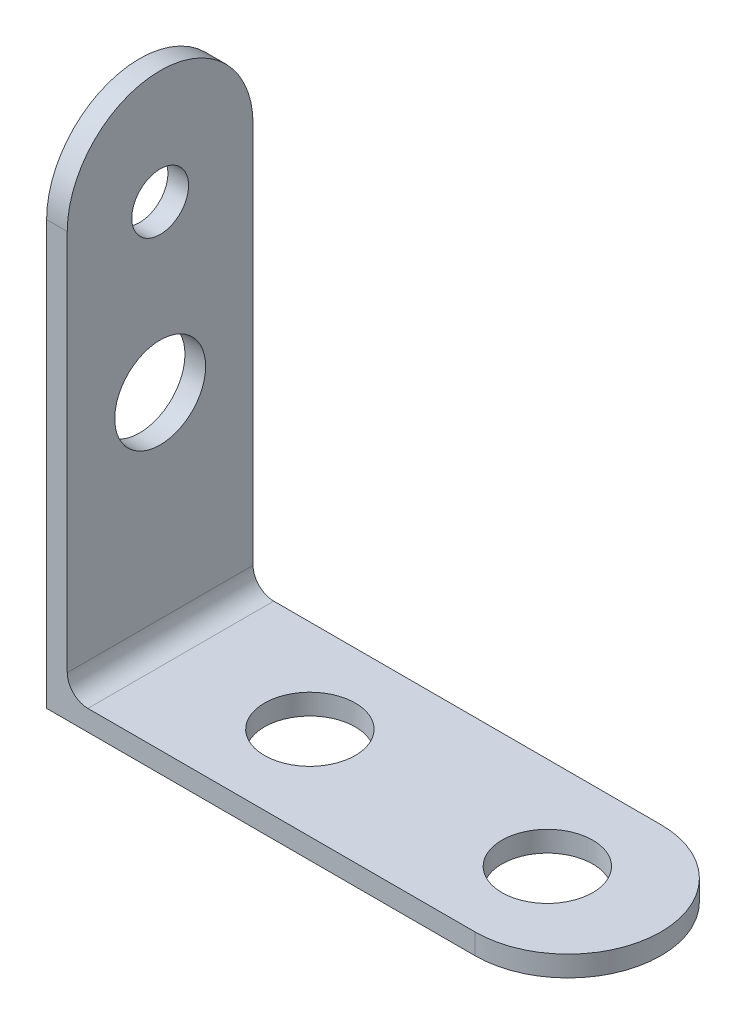
SolidWorks part; units mm, degrees
ref_plane "前视基准面" through (0, 0, 0) normal (0, 0, 1) x (1, 0, 0)
ref_plane "上视基准面" through (0, 0, 0) normal (0, 1, 0) x (1, 0, 0)
ref_plane "右视基准面" through (0, 0, 0) normal (1, 0, 0) x (0, 0, -1)
other "Configuration Table"
sketch "草图1" plane through (0, 0, 0) normal (0, 0, 1) x (1, 0, 0)
  line L0 (0, 0) -> (-48.5, 0)
  line L1 (-48.5, 0) -> (-48.5, 48)
  line L2 (-48.5, 48) -> (-50.5, 48)
  line L3 (-50.5, 48) -> (-50.5, -2)
  line L4 (-50.5, -2) -> (0, -2)
  line L5 (0, -2) -> (0, 0)
  point P6 (-49.5, 48)
  dimension "D1" = 50.5
  dimension "D2" = 2
  dimension "D3" = 2
  dimension "D4" = 50
extrude "凸台-拉伸1" add sketch "草图1" along normal blind 18
fillet "圆角1" radius 2 1 edges at (-48.5, 0, 9)
sketch "草图2" plane through (-48.5, 0, 0) normal (1, 0, 0) x (0, 0, -1)
  line L0 (-18, 48) -> (-18, 39)
  line L1 (-18, 2) -> (-18, 48) construction
  line L2 (0, 48) -> (0, 39)
  line L3 (0, 2) -> (0, 48) construction
  line L4 (-9, 48) -> (-9, 37)
  line L5 (-9, 37) -> (-9, 21)
  line L6 (-18, 48) -> (0, 48) construction
  arc A0 (-18, 39) -> (0, 39) centre (-9, 39) cw
  circle A1 centre (-9, 37) radius 2.75
  circle A2 centre (-9, 21) radius 4.4
  dimension "D1" = 11
  dimension "D2" = 5.5
  dimension "D3" = 8.8
  dimension "D4" = 16
extrude "切除-拉伸1" cut sketch "草图2" against normal blind 10
sketch "草图3" plane through (0, 0, 0) normal (0, 1, 0) x (1, 0, 0)
  line L0 (0, 0) -> (-9, 0)
  line L1 (0, 0) -> (-46.5, 0) construction
  line L2 (0, -9) -> (-11, -9)
  line L4 (-11, -9) -> (-34, -9)
  arc A0 (-9, 0) -> (-9, -18) centre (-9, -9) cw
  circle A1 centre (-11, -9) radius 4.4
  circle A2 centre (-34, -9) radius 4.4
  dimension "D1" = 11
  dimension "D2" = 8.8
  dimension "D3" = 8.8
extrude "切除-拉伸2" cut sketch "草图3" against normal blind 10
